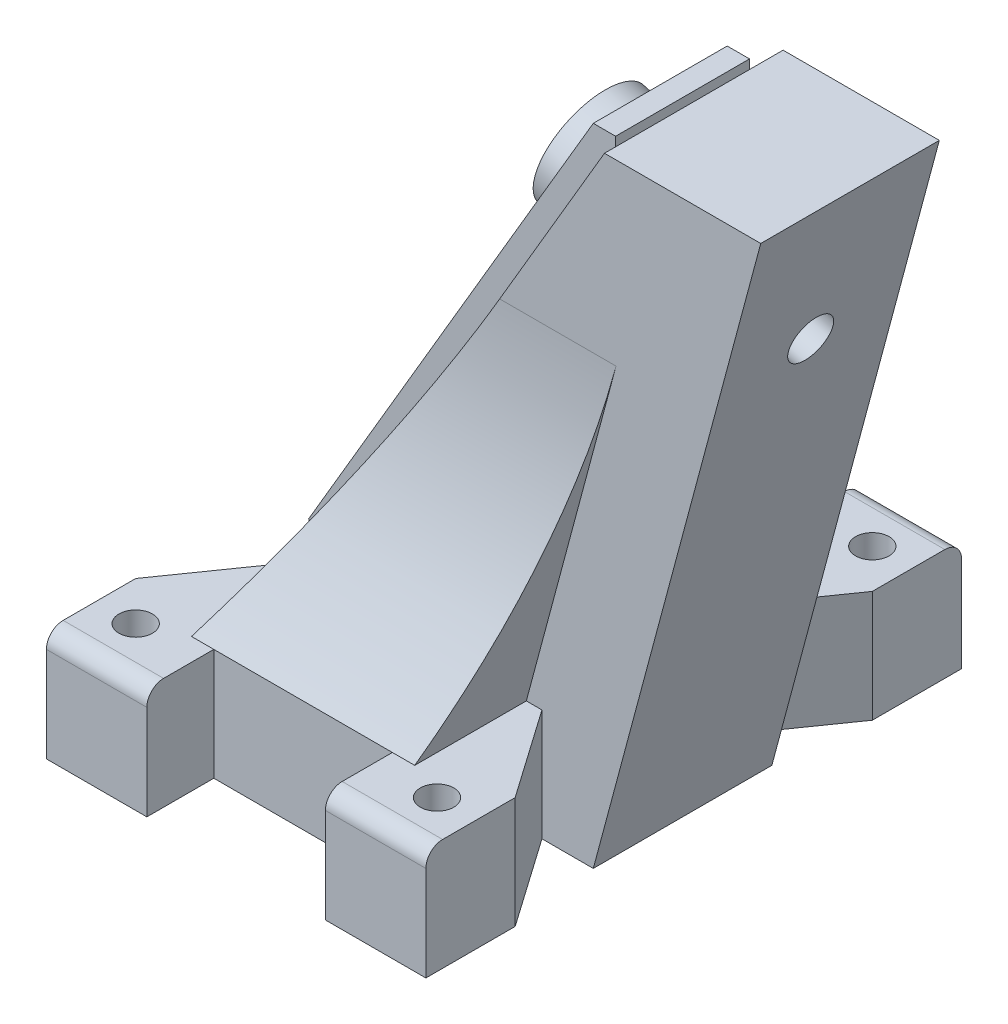
SolidWorks part; units mm, degrees
ref_plane "Front" through (0, 0, 0) normal (0, 0, 1) x (1, 0, 0)
ref_plane "Top" through (0, 0, 0) normal (0, 1, 0) x (1, 0, 0)
ref_plane "Right" through (0, 0, 0) normal (1, 0, 0) x (0, 0, -1)
sketch "Sketch1" plane through (0, 0, 0) normal (0, 0, 1) x (1, 0, 0)
  line L0 (0, 0) -> (-26, 0)
  line L1 (0, 0) -> (15.0052, 56)
  line L2 (15.0052, 56) -> (1.0052, 56)
  line L3 (1.0052, 56) -> (-26, 10)
  line L4 (-26, 10) -> (-26, 0)
  dimension "D1" = 26
  dimension "D2" = 56
  dimension "D3" = 10
  dimension "D4" = 75
  dimension "D5" = 14
extrude "Boss-Extrude1" add sketch "Sketch1" along normal blind 36
sketch "Sketch2" plane through (-26, 3.423, 0) normal (1, 0, 0) x (0, 0, -1)
  line L0 (-26, 52.577) -> (-26, 36.577)
  line L1 (-36, 52.577) -> (0, 52.577) construction
  line L2 (-36, -3.423) -> (-36, 52.577) construction
  line L3 (-36, 6.577) -> (0, 6.577) construction
  line L4 (-36, 6.577) -> (0, 6.577)
  line L5 (-18, 52.577) -> (-18, 55.5539) construction
  line L6 (-10, 52.577) -> (-10, 36.577)
  line L7 (-36, 52.577) -> (-36, 6.577)
  line L8 (0, 6.577) -> (0, 52.577)
  line L9 (0, 52.577) -> (-10, 52.577)
  line L10 (-26, 52.577) -> (-36, 52.577)
  arc A0 (-36, 6.577) -> (-26, 36.577) centre (-76, 36.577) ccw
  arc A1 (0, 6.577) -> (-10, 36.577) centre (40, 36.577) cw
  dimension "D1" = 10
  dimension "D2" = 30
extrude "Cut-Extrude1" cut sketch "Sketch2" along normal up to next
ref_plane "Plane1" through (-6, 0, 0) normal (-1, 0, 0) x (0, 0, 1)
sketch "Sketch5" plane through (-6, 0, 0) normal (-1, 0, 0) x (0, 0, 1)
  line L13 (36, 0) -> (0, 0) construction
  line L14 (36, 10) -> (26, 10)
  line L15 (36, 10) -> (36, 0)
  line L16 (36, 0) -> (26, 0)
  line L17 (26, 10) -> (26, 0)
  line L18 (36, 10) -> (26, 0) construction
  line L19 (36, 0) -> (26, 10) construction
  line L21 (10, 0) -> (0, 0)
  line L22 (10, 0) -> (10, 10)
  line L23 (10, 10) -> (0, 10)
  line L24 (0, 0) -> (0, 10)
  line L25 (10, 0) -> (0, 10) construction
  line L26 (10, 10) -> (0, 0) construction
  point P4 (31, 5)
  point P11 (5, 5)
extrude "Cut-Extrude4" cut sketch "Sketch5" against normal through all
sketch "Sketch6" plane through (0, 0, 0) normal (0.9659, -0.2588, 0) x (0, 0, -1)
  line L1 (-26, 57.9755) -> (-36, 57.9755)
  line L2 (-26, 57.9755) -> (-26, 8.1063)
  line L3 (-26, 8.1063) -> (-36, 8.1063)
  line L4 (-36, 57.9755) -> (-36, 8.1063)
  line L5 (-26, 57.9755) -> (-36, 8.1063) construction
  line L6 (-26, 8.1063) -> (-36, 57.9755) construction
  line L7 (-10, 57.9755) -> (0, 57.9755)
  line L8 (-10, 57.9755) -> (-10, 8.1063)
  line L9 (-10, 8.1063) -> (0, 8.1063)
  line L10 (0, 57.9755) -> (0, 8.1063)
  line L11 (-10, 57.9755) -> (0, 8.1063) construction
  line L12 (-10, 8.1063) -> (0, 57.9755) construction
  point P4 (-31, 33.0409)
  point P11 (-5, 33.0409)
extrude "Cut-Extrude5" cut sketch "Sketch6" against normal up to vertex (8.3837 mm away)
sketch "Sketch7" plane through (0, 0, 0) normal (0, -1, 0) x (1, 0, 0)
  line L0 (-26, 24) -> (-33, 34)
  line L1 (-26, 36) -> (-26, 0) construction
  line L2 (-33, 34) -> (-33, 42)
  line L3 (-33, 42) -> (-24, 42)
  line L4 (-24, 42) -> (-24, 36)
  line L5 (-26, 36) -> (-6, 36) construction
  line L6 (-29.5, 42) -> (-29.5, 37.5) construction
  line L7 (-26, 24) -> (-26, 36)
  line L8 (-26, 36) -> (-24, 36)
  line L9 (-26, 18) -> (-19.9744, 18) construction
  line L10 (-26, 0) -> (-33, -6) construction
  line L11 (-26, 0) -> (-24, 0)
  line L12 (-26, 12) -> (-26, 0)
  line L13 (-24, -6) -> (-24, 0)
  line L14 (-33, -6) -> (-24, -6)
  line L15 (-33, 2) -> (-33, -6)
  line L16 (-26, 12) -> (-33, 2)
  line L17 (-16, 36) -> (-16, 34.6748) construction
  line L18 (-6, 0) -> (1, -6) construction
  line L19 (-6, 18) -> (-12.0256, 18) construction
  line L20 (-6, 36) -> (1, 42) construction
  line L21 (-6, 12) -> (1, 2)
  line L22 (1, 2) -> (1, -6)
  line L23 (1, -6) -> (-8, -6)
  line L24 (-8, -6) -> (-8, 0)
  line L25 (-6, 12) -> (-6, 0)
  line L26 (-6, 0) -> (-8, 0)
  line L27 (-6, 36) -> (-8, 36)
  line L28 (-6, 24) -> (-6, 36)
  line L29 (-8, 42) -> (-8, 36)
  line L30 (1, 42) -> (-8, 42)
  line L31 (1, 34) -> (1, 42)
  line L32 (-6, 24) -> (1, 34)
  circle A0 centre (-29.5, 37.5) radius 1.5
  circle A1 centre (-29.5, -1.5) radius 1.5
  circle A2 centre (-2.5, -1.5) radius 1.5
  circle A3 centre (-2.5, 37.5) radius 1.5
  dimension "D6" = 3
  dimension "D8" = 4.5
  dimension "D1" = 12
  dimension "D2" = 2
  dimension "D3" = 6
  dimension "D4" = 2
  dimension "D5" = 9
  dimension "D7" = 3.5
extrude "Boss-Extrude2" add sketch "Sketch7" against normal blind 10
ref_plane "Plane2" through (0, 0, 18) normal (0, 0, 1) x (1, 0, 0)
sketch "Sketch8" plane through (0, 0, 18) normal (0, 0, 1) x (1, 0, 0)
  line L0 (-26, 10) -> (-26, 0) construction
  line L1 (-26, 10) -> (-26, 0)
  line L2 (-26, 5) -> (-27.5, 12.383)
  line L3 (-27.5, 12.383) -> (-2, 55.8191)
  line L4 (-2, 55.8191) -> (0, 55.8191)
  line L5 (0, 55.8191) -> (0, 54.2878)
  line L6 (1.0052, 56) -> (-8.3879, 40) construction
  line L7 (-8.3879, 40) -> (-26, 10) construction
  line L8 (-26, 10) -> (0, 54.2878)
  dimension "D1" = 2.5
  dimension "D2" = 1.5
  dimension "D3" = 2
extrude "Boss-Extrude3" add sketch "Sketch8" along normal mid plane 12 contours L1 L8 L5 L4 L3 L2
sketch "Sketch9" plane through (0, 0, 0) normal (-0.9659, 0.2588, 0) x (0, 0, -1)
  line L0 (-18, -54.352) -> (-18, -44.352) construction
  line L1 (-26, -54.352) -> (-10, -54.352) construction
  circle A0 centre (-18, -44.352) radius 5
  dimension "D2" = 10
  dimension "D1" = 10
extrude "Boss-Extrude4" add sketch "Sketch9" along normal blind 20.4
sketch "Sketch12" plane through (-19.7049, 5.2799, 0) normal (-0.9659, 0.2588, 0) x (0, 0, 1)
  circle A0 centre (18, 44.352) radius 2
  dimension "D1" = 4
extrude "Cut-Extrude7" cut sketch "Sketch12" against normal up to next
fillet "Fillet1" radius 1.5 4 edges at (-3.5, 10, 42) (-3.5, 10, -6) (-28.5, 10, -6) (-28.5, 10, 42)
